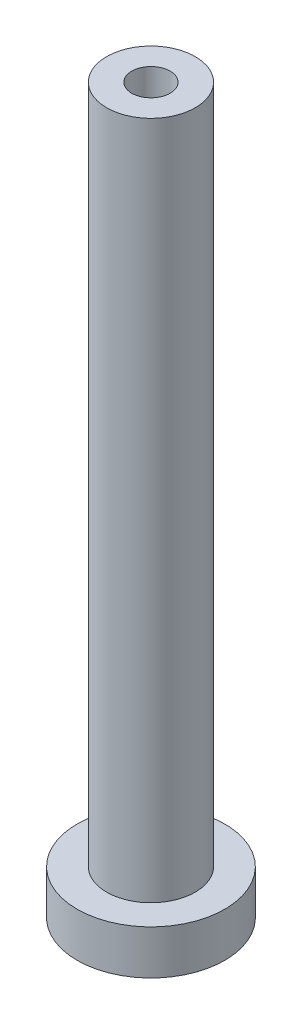
SolidWorks part; units mm, degrees
ref_plane "前视基准面" through (0, 0, 0) normal (0, 0, 1) x (1, 0, 0)
ref_plane "上视基准面" through (0, 0, 0) normal (0, 1, 0) x (1, 0, 0)
ref_plane "右视基准面" through (0, 0, 0) normal (1, 0, 0) x (0, 0, -1)
other "Configuration Table"
sketch "草图1" plane through (0, 0, 0) normal (1, 0, 0) x (0, 0, -1)
  line L0 (0, 0) -> (0, 1.5)
  line L1 (0, 1.5) -> (1, 1.5)
  line L2 (1, 1.5) -> (1, 24.5)
  line L3 (1, 24.5) -> (1.85, 24.5)
  line L4 (1.85, 24.5) -> (1.85, 16.5)
  line L5 (1.85, 16.5) -> (2.5, 16.5)
  line L6 (2.5, 16.5) -> (2.5, 0)
  line L7 (2.5, 0) -> (0, 0)
  dimension "D1" = 2.5
  dimension "D2" = 1.5
  dimension "D3" = 0.65
  dimension "D4" = 1.5
  dimension "D5" = 23
  dimension "D6" = 8
revolve "旋转1" add sketch "草图1" angle 360 about L6
